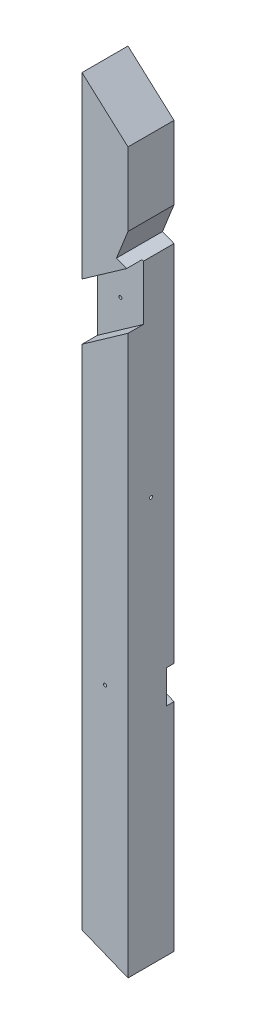
SolidWorks part; units mm, degrees
material "Pine"
ref_plane "Front Plane" through (0, 0, 0) normal (0, 0, 1) x (1, 0, 0)
ref_plane "Top Plane" through (0, 0, 0) normal (0, 1, 0) x (1, 0, 0)
ref_plane "Right Plane" through (0, 0, 0) normal (1, 0, 0) x (0, 0, -1)
sketch "Sketch1" plane through (0, 0, 0) normal (0, 1, 0) x (1, 0, 0)
  line L1 (-75, 75) -> (75, 75)
  line L2 (-75, 75) -> (-75, -75)
  line L3 (-75, -75) -> (75, -75)
  line L4 (75, 75) -> (75, -75)
  line L5 (-75, 75) -> (75, -75) construction
  line L6 (-75, -75) -> (75, 75) construction
  point P0 (0, 0)
  dimension "D1" = 150
  dimension "D2" = 150
extrude "Boss-Extrude1" add sketch "Sketch1" along normal mid plane 2500
sketch "Sketch2" plane through (0, 0, 75) normal (0, 0, 1) x (1, 0, 0)
  circle A0 centre (0, 610) radius 5
  circle A1 centre (0, -460) radius 5
  dimension "D1" = 10
  dimension "D2" = 610
  dimension "D3" = 460
extrude "Cut-Extrude1" cut sketch "Sketch2" against normal through all
sketch "Sketch3" plane through (0, 0, 75) normal (0, 0, 1) x (1, 0, 0)
  line L0 (-75, 1232.7038) -> (75, 1097.5937)
  line L1 (-75, 1250) -> (-75, -1250) construction
  line L2 (-462.1235, 1581.399) -> (652.411, 577.5002) construction
  line L3 (75, 1250) -> (75, -1250) construction
  line L4 (75, 1097.5937) -> (75, 1250)
  line L5 (75, 1250) -> (-75, 1250)
  line L6 (-75, 1250) -> (-75, 1232.7038)
extrude "RoofCut" cut sketch "Sketch3" against normal through all
sketch "Sketch4" plane through (0, 0, 75) normal (0, 0, 1) x (1, 0, 0)
  line L0 (75, 858.8784) -> (37.5225, 764.8707)
  line L1 (75, 1097.5937) -> (75, -1250) construction
  line L2 (37.5225, 764.8707) -> (75, 749.7209)
  line L3 (37.5225, 764.8707) -> (130.234, 727.3932) construction
  line L4 (75, 749.7209) -> (75, 858.8784)
extrude "TopCut" cut sketch "Sketch4" against normal through all
sketch "Sketch5" plane through (75, 0, 0) normal (1, 0, 0) x (0, 0, -1)
  circle A0 centre (0, 70) radius 5
  dimension "D1" = 10
  dimension "D2" = 70
extrude "Cut-Extrude4" cut sketch "Sketch5" against normal through all
sketch "Sketch7" plane through (0, 0, 75) normal (0, 0, 1) x (1, 0, 0)
  line L0 (-75, 649.4867) -> (-75, 465.3023)
  line L1 (-75, 1232.7038) -> (-75, -1250) construction
  line L2 (402.7675, 802.3625) -> (-1566.0561, -586.6228) construction
  line L3 (-75, 465.3023) -> (75, 571.1258)
  line L4 (75, 749.7209) -> (75, -1250) construction
  line L5 (75, 571.1258) -> (75, 754.9506)
  line L6 (75, 33.5414) -> (75, 882.9223) construction
  line L7 (75, 754.9506) -> (-75, 649.4867)
extrude "Cut-Extrude5" cut sketch "Sketch7" against normal blind 50
sketch "Sketch8" plane through (0, 0, -75) normal (0, 0, -1) x (-1, 0, 0)
  line L0 (-78.6084, -545.7072) -> (75, -483.6129)
  line L1 (75, 1232.7038) -> (75, -1250) construction
  line L2 (1080.2862, -77.238) -> (-78.6084, -545.7072) construction
  line L3 (75, -483.6129) -> (75, -375.7514)
  line L4 (1042.8087, 15.4735) -> (-116.0859, -452.9956) construction
  line L5 (75, -375.7514) -> (-75, -436.3871)
  line L6 (-75, 749.7209) -> (-75, -1250) construction
  line L7 (-75, -436.3871) -> (-78.6084, -545.7072)
extrude "Cut-Extrude6" cut sketch "Sketch8" against normal blind 25
sketch "Sketch9" plane through (0, 0, 75) normal (0, 0, 1) x (1, 0, 0)
  line L0 (-75, -1189.3643) -> (75, -1250)
  line L1 (-75, 465.3023) -> (-75, -1250) construction
  line L2 (-1853.7116, -470.3416) -> (464.0776, -1407.2799) construction
  line L3 (75, -1250) -> (-75, -1250)
  line L4 (-75, -1250) -> (-75, -1189.3643)
extrude "Cut-Extrude7" cut sketch "Sketch9" against normal through all
